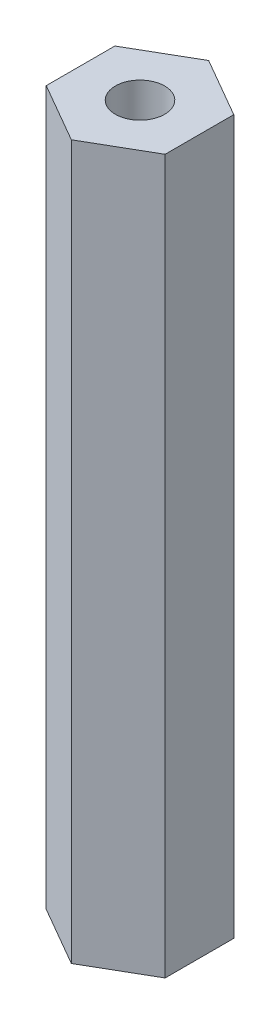
SolidWorks part; units mm, degrees
ref_plane "Front Plane" through (0, 0, 0) normal (0, 0, 1) x (1, 0, 0)
ref_plane "Top Plane" through (0, 0, 0) normal (0, 1, 0) x (1, 0, 0)
ref_plane "Right Plane" through (0, 0, 0) normal (1, 0, 0) x (0, 0, -1)
sketch "Sketch1" plane through (0, 0, 0) normal (0, 1, 0) x (1, 0, 0)
  line L1 (0, 7.3323) -> (-6.35, 3.6662)
  line L2 (-6.35, 3.6662) -> (-6.35, -3.6662)
  line L3 (-6.35, -3.6662) -> (0, -7.3323)
  line L4 (0, -7.3323) -> (6.35, -3.6662)
  line L5 (6.35, -3.6662) -> (6.35, 3.6662)
  line L6 (6.35, 3.6662) -> (0, 7.3323)
  circle A0 centre (0, 0) radius 6.35 construction
  circle A1 centre (0, 0) radius 2.6289
  dimension "D1" = 12.7
  dimension "D2" = 5.2578
extrude "Boss-Extrude1" add sketch "Sketch1" along normal blind 76.2
